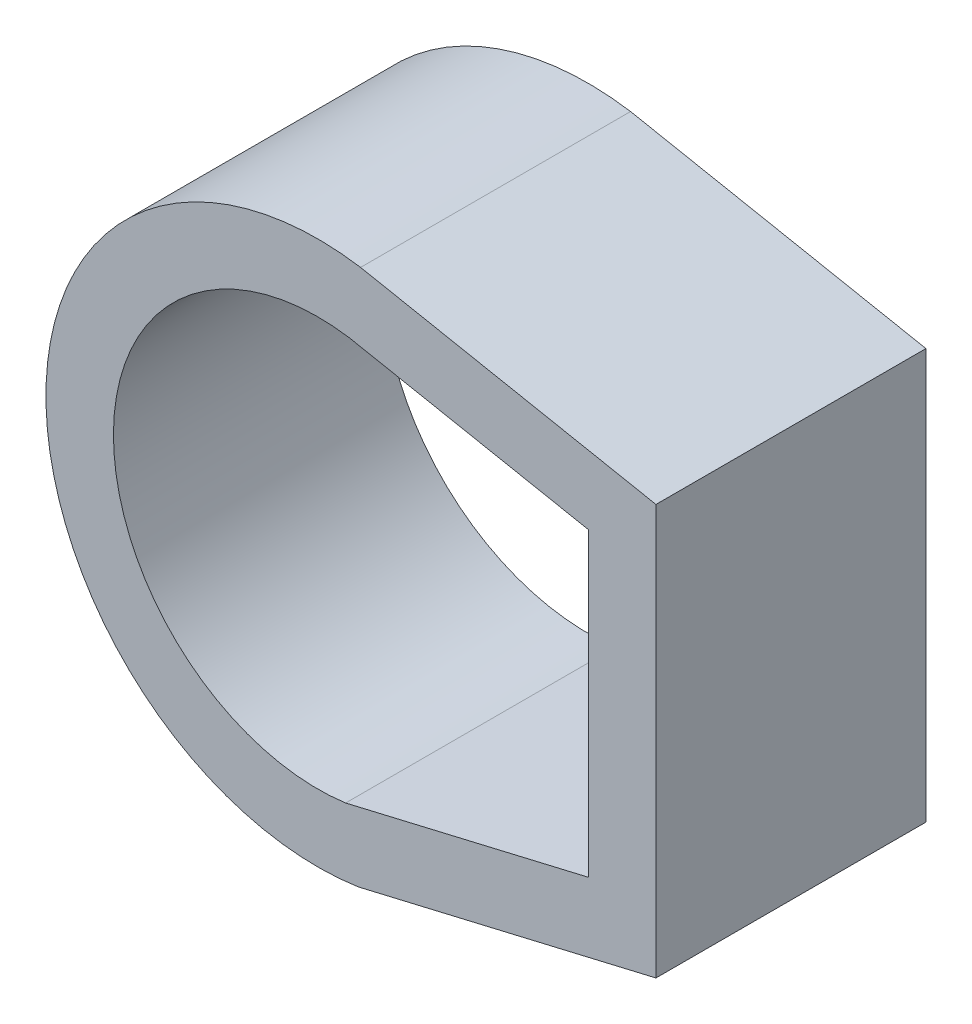
SolidWorks part; units mm, degrees
ref_plane "Alzado" through (0, 0, 0) normal (0, 0, 1) x (1, 0, 0)
ref_plane "Planta" through (0, 0, 0) normal (0, 1, 0) x (1, 0, 0)
ref_plane "Vista lateral" through (0, 0, 0) normal (1, 0, 0) x (0, 0, -1)
sketch "Croquis3" plane through (0, 0, 0) normal (0, 0, 1) x (1, 0, 0)
  line L218 (-8.1572, 2.8211) -> (-26.7313, 6.4418) construction
  line L219 (-8.1572, 2.8211) -> (-8.1572, -21.0951) construction
  line L220 (-8.1572, -21.0951) -> (-26.9615, -25.5138) construction
  line L239 (-4.1572, 6.1166) -> (-26.0389, 10.3821)
  line L254 (-4.1572, 6.1166) -> (-4.1572, -24.2641)
  line L255 (-4.1572, -24.2641) -> (-26.2158, -29.4475)
  line L256 (-9.1572, 1.9972) -> (-26.903, 5.4564)
  line L257 (-9.1572, 1.9972) -> (-9.1572, -20.3028)
  line L258 (-9.1572, -20.3028) -> (-27.1447, -24.5296)
  arc A14 (-26.9615, -25.5138) -> (-26.7313, 6.4418) centre (-29.1957, -9.5191) cw construction
  arc A18 (-26.2158, -29.4475) -> (-26.0389, 10.3821) centre (-29.1957, -9.5191) cw
  arc A21 (-27.1447, -24.5296) -> (-26.903, 5.4564) centre (-29.1957, -9.5191) cw
  dimension "D18" = 18.8042
  dimension "D15" = 18.574
  dimension "D3" = 4
  dimension "D29" = 16.15
  dimension "D4" = 1
  dimension "D21" = 23.9161
extrude "Saliente-Extruir1" add sketch "Croquis3" along normal blind 20
